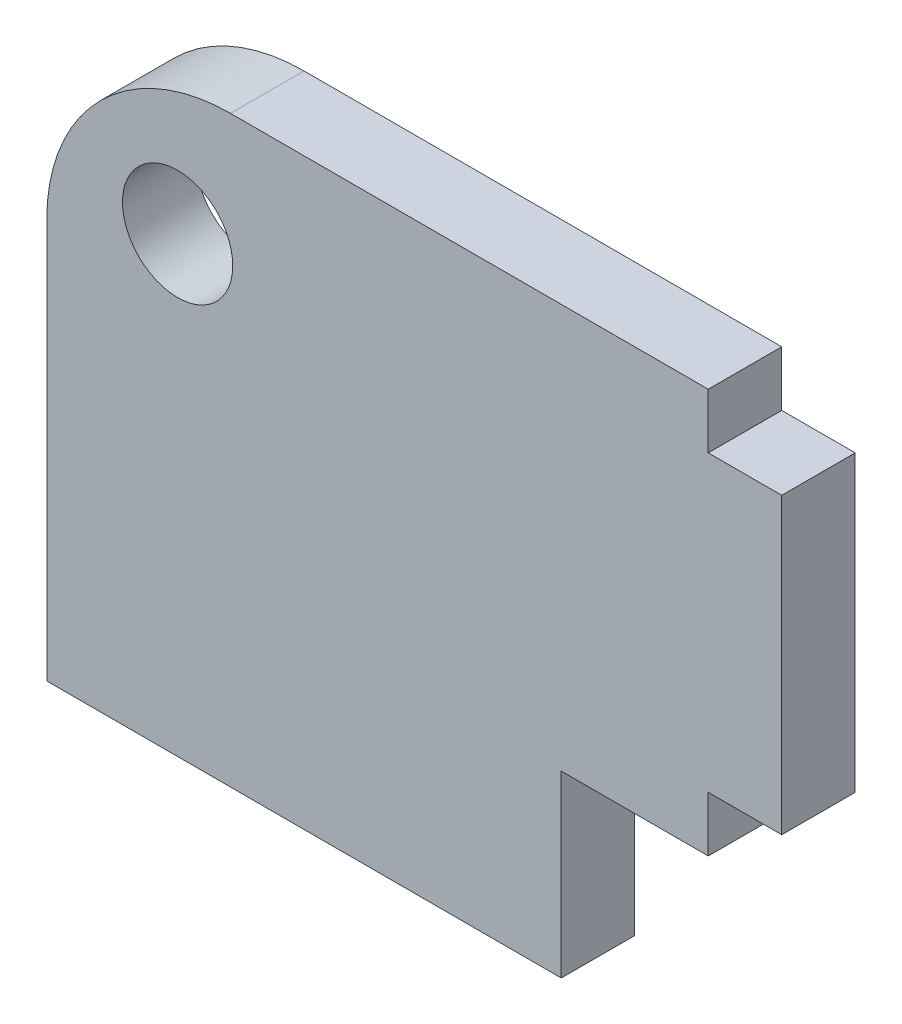
SolidWorks part; units mm, degrees
ref_plane "Front Plane" through (0, 0, 0) normal (0, 0, 1) x (1, 0, 0)
ref_plane "Top Plane" through (0, 0, 0) normal (0, 1, 0) x (1, 0, 0)
ref_plane "Right Plane" through (0, 0, 0) normal (1, 0, 0) x (0, 0, -1)
sketch "Sketch1" plane through (0, 0, 0) normal (0, 0, 1) x (1, 0, 0)
  line L0 (10, -1.5622) -> (8, -1.5622)
  line L1 (4, -7.9378) -> (-10, -7.9378)
  line L2 (4, -7.9378) -> (4, -3.0622)
  line L3 (10, 6.4378) -> (10, -1.5622)
  line L4 (-5, 7.9378) -> (8, 7.9378)
  line L5 (8, 6.4378) -> (8, 7.9378)
  line L6 (10, 6.4378) -> (8, 6.4378)
  line L7 (-10, -7.9378) -> (-10, 2.9378)
  line L8 (8, -1.5622) -> (8, -3.0622)
  line L9 (8, -3.0622) -> (4, -3.0622)
  arc A0 (-10, 2.9378) -> (-5, 7.9378) centre (-5, 2.9378) cw
  circle A2 centre (-6.4393, 4.3772) radius 1.5
  dimension "D6" = 5
  dimension "D1" = 14
  dimension "D2" = 1.5
  dimension "D3" = 2
  dimension "D4" = 8
  dimension "D5" = 1.5
extrude "Boss-Extrude1" add sketch "Sketch1" along normal blind 2
